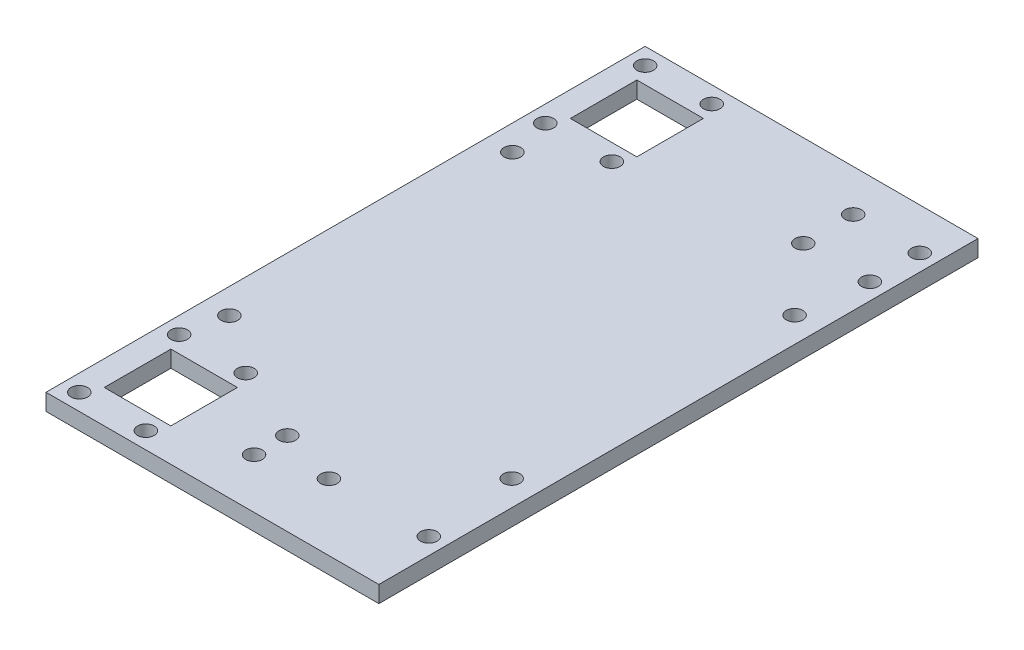
SolidWorks part; units mm, degrees
material "6061 Alloy"
ref_plane "Front Plane" through (0, 0, 0) normal (0, 0, 1) x (1, 0, 0)
ref_plane "Top Plane" through (0, 0, 0) normal (0, 1, 0) x (1, 0, 0)
ref_plane "Right Plane" through (0, 0, 0) normal (1, 0, 0) x (0, 0, -1)
sketch "Sketch1" plane through (0, 0, 0) normal (0, 1, 0) x (1, 0, 0)
  line L0 (-83.1428, 0) -> (76.5856, 0) construction
  line L1 (-63.5, -114.3) -> (63.5, -114.3)
  line L2 (-63.5, -114.3) -> (-63.5, 114.3)
  line L3 (-63.5, 114.3) -> (63.5, 114.3)
  line L4 (63.5, -114.3) -> (63.5, 114.3)
  line L5 (-63.5, -114.3) -> (63.5, 114.3) construction
  line L6 (-63.5, 114.3) -> (63.5, -114.3) construction
  line L7 (0, 125.4393) -> (0, -149.1536) construction
  line L8 (-53.975, -101.6) -> (-53.9407, -76.2)
  line L9 (-53.975, 101.6) -> (-53.9407, 76.2)
  line L10 (-53.975, 101.6) -> (-28.575, 101.6)
  line L11 (-28.575, 101.6) -> (-28.575, 76.2)
  line L12 (-28.575, 76.2) -> (-53.9407, 76.2)
  line L13 (-53.975, -101.6) -> (-28.575, -101.6)
  line L14 (-28.575, -101.6) -> (-28.575, -76.2)
  line L15 (-28.575, -76.2) -> (-53.9407, -76.2)
  circle A0 centre (-57.15, 107.95) radius 3.175
  circle A1 centre (-57.15, 69.85) radius 3.175
  circle A2 centre (-31.75, 107.95) radius 3.175
  circle A3 centre (-31.75, 69.85) radius 3.175
  circle A4 centre (-31.75, -69.85) radius 3.175
  circle A5 centre (-57.15, -69.85) radius 3.175
  circle A6 centre (-31.75, -107.95) radius 3.175
  circle A7 centre (-57.15, -107.95) radius 3.175
  circle A8 centre (57.15, 98.425) radius 3.175
  circle A9 centre (31.75, 98.425) radius 3.175
  circle A10 centre (57.15, 79.375) radius 3.175
  circle A11 centre (31.75, 79.375) radius 3.175
  circle A12 centre (57.15, -88.9) radius 3.175
  circle A13 centre (19.05, -88.9) radius 3.175
  circle A14 centre (-53.848, -53.975) radius 3.175
  circle A15 centre (-53.848, 53.975) radius 3.175
  circle A16 centre (53.848, -53.975) radius 3.175
  circle A17 centre (53.848, 53.975) radius 3.175
  circle A18 centre (-3.175, -82.55) radius 3.175
  circle A19 centre (-3.175, -95.25) radius 3.175
  point P0 (0, 0)
  dimension "D1" = 6.35
  dimension "D2" = 6.35
  dimension "D3" = 6.35
  dimension "D4" = 38.1
  dimension "D5" = 228.6
  dimension "D6" = 127
  dimension "D7" = 25.4
  dimension "D8" = 25.4
  dimension "D9" = 25.4
  dimension "D10" = 15.875
  dimension "D11" = 6.35
  dimension "D12" = 25.4
  dimension "D13" = 19.05
  dimension "D14" = 25.4
  dimension "D15" = 38.1
  dimension "D16" = 53.975
  dimension "D17" = 9.652
  dimension "D18" = 60.325
  dimension "D19" = 12.7
  dimension "D20" = 19.05
extrude "Boss-Extrude1" add sketch "Sketch1" along normal blind 6.35
sketch "Sketch2" plane through (0, 0, 114.3) normal (0, 0, 1) x (1, 0, 0)
  line L0 (-3.8449, 2.9921) -> (-63.5579, 44.8036) construction
  line L1 (-63.5, 6.35) -> (63.5, 6.35) construction
  dimension "D1" = 35
